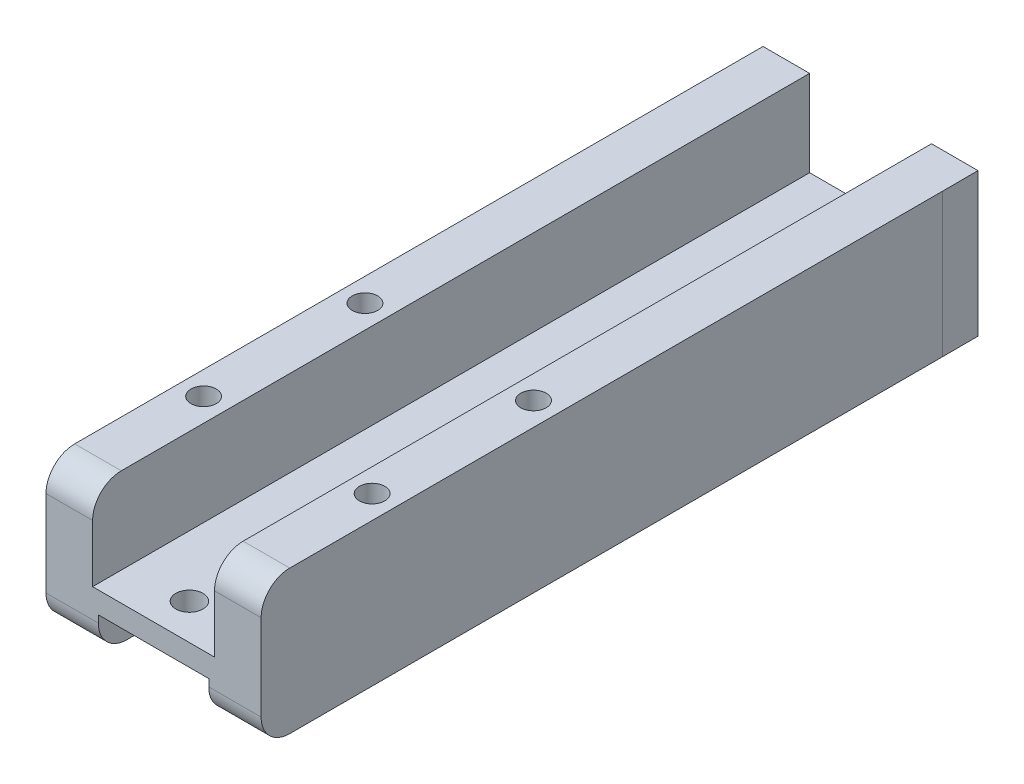
SolidWorks part; units mm, degrees
ref_plane "Front Plane" through (0, 0, 0) normal (0, 0, 1) x (1, 0, 0)
ref_plane "Top Plane" through (0, 0, 0) normal (0, 1, 0) x (1, 0, 0)
ref_plane "Right Plane" through (0, 0, 0) normal (1, 0, 0) x (0, 0, -1)
sketch "Sketch1" plane through (0, 0, 0) normal (0, 1, 0) x (1, 0, 0)
  line L0 (-19.05, 60.325) -> (-19.05, 66.675)
  line L1 (-19.05, -60.325) -> (19.05, -60.325)
  line L2 (-19.05, -60.325) -> (-19.05, 60.325)
  line L4 (19.05, -60.325) -> (19.05, 60.325)
  line L5 (-19.05, -60.325) -> (19.05, 60.325) construction
  line L6 (-19.05, 60.325) -> (19.05, -60.325) construction
  line L8 (19.0295, 66.675) -> (19.05, 60.325)
  line L9 (-19.05, 66.675) -> (19.0295, 66.675)
  line L10 (-22, 66.675) -> (22, 66.675) construction
  point P0 (0, 0)
  dimension "D1" = 38.1
  dimension "D2" = 120.65
  dimension "D3" = 6.35
extrude "Boss-Extrude1" add sketch "Sketch1" along normal blind 38.1
sketch "Sketch2" plane through (0, 38.1, 0) normal (0, 1, 0) x (1, 0, 0)
  line L1 (-10.795, -158.75) -> (10.795, -158.75)
  line L2 (-10.795, -158.75) -> (-10.795, 95.25)
  line L3 (-10.795, 95.25) -> (10.795, 95.25)
  line L4 (10.795, -158.75) -> (10.795, 95.25)
  line L5 (-10.795, -158.75) -> (10.795, 95.25) construction
  line L6 (-10.795, 95.25) -> (10.795, -158.75) construction
  point P0 (0, -31.75)
  dimension "D1" = 254
  dimension "D2" = 21.59
  dimension "D3" = 31.75
extrude "Cut-Extrude1" cut sketch "Sketch2" against normal blind 27.94
sketch "Sketch3" plane through (19.05, 0, 0) normal (1, 0, 0) x (0, 0, -1)
  line L0 (-60.325, 38.1) -> (-60.325, 0) construction
  line L1 (-60.325, 0) -> (60.325, 0) construction
  circle A0 centre (-28.575, 29.21) radius 5.08
  circle A1 centre (34.925, 29.21) radius 5.08
  dimension "D1" = 10.16
  dimension "D2" = 31.75
  dimension "D3" = 29.21
  dimension "D4" = 63.5
sketch "Sketch11" plane through (-19.05, 0, 0) normal (-1, 0, 0) x (0, 0, 1)
  line L0 (60.325, 25.4) -> (35.0008, 25.4)
  line L1 (60.325, 38.1) -> (60.325, 0) construction
  line L3 (-66.675, 0) -> (60.325, 0) construction
  line L7 (-41.6975, 25.4) -> (-60.4984, 25.4)
  line L8 (21.8025, 25.4) -> (-28.4992, 25.4)
  line L10 (-60.4984, 38.1) -> (60.325, 38.1)
  line L11 (60.325, 38.1) -> (60.325, 25.4)
  line L12 (21.8025, 25.4) -> (35.0008, 25.4)
  line L13 (-28.4992, 25.4) -> (-41.6975, 25.4)
  line L14 (-60.4984, 25.4) -> (-66.675, 25.4)
  line L15 (-66.675, 38.1) -> (-66.675, 0) construction
  line L17 (-66.675, 38.1) -> (-60.4984, 38.1)
  line L18 (-66.675, 38.1) -> (-71.3773, 38.1)
  line L19 (-71.3773, 38.1) -> (-71.3773, 25.4)
  line L20 (-71.3773, 25.4) -> (-66.675, 25.4)
  dimension "D2" = 25.4
  dimension "D3" = 12.7
extrude "Cut-Extrude8" cut sketch "Sketch11" against normal through all
sketch "Sketch12" plane through (0, 0, 60.325) normal (0, 0, 1) x (1, 0, 0)
  line L1 (-9.779, -6.35) -> (9.779, -6.35)
  line L2 (-9.779, -6.35) -> (-9.779, 6.35)
  line L3 (-9.779, 6.35) -> (9.779, 6.35)
  line L4 (9.779, -6.35) -> (9.779, 6.35)
  line L5 (-9.779, -6.35) -> (9.779, 6.35) construction
  line L6 (-9.779, 6.35) -> (9.779, -6.35) construction
  point P0 (0, 0)
  dimension "D1" = 19.558
  dimension "D2" = 12.7
extrude "Cut-Extrude9" cut sketch "Sketch12" against normal through all
sketch "Sketch13" plane through (0, 10.16, 0) normal (0, 1, 0) x (1, 0, 0)
  line L0 (10.795, -60.325) -> (-10.795, -60.325) construction
  line L2 (0, 47.625) -> (0, -53.975) construction
  circle A0 centre (0, -53.975) radius 2.413
  circle A1 centre (0, 47.625) radius 2.413
  circle A2 centre (0, -3.175) radius 2.413
  dimension "D1" = 4.826
  dimension "D2" = 6.35
  dimension "D3" = 101.6
extrude "Cut-Extrude10" cut sketch "Sketch13" against normal through all
sketch "Sketch14" plane through (0, 25.4, 0) normal (0, 1, 0) x (1, 0, 0)
  point P0 (-14.9225, -36.5306)
  point P1 (-14.9225, -7.9556)
  point P3 (14.9225, -7.9556)
  point P5 (14.9225, -36.5306)
hole_wizard "#8 Clearance Hole1" positions "Sketch14" profile "Sketch16" hole size "#8" standard "ANSI Inch" end condition through all
sketch "Sketch16" plane through (-14.9225, 25.4, 36.5306) normal (1, 0, 0) x (0, 0, 1)
  line L0 (0, 0) -> (0, 25.4)
  line L1 (0, 25.4) -> (2.2479, 25.4)
  line L2 (2.2479, 25.4) -> (2.2479, 0)
  line L5 (2.2479, 0) -> (0, 0)
  line L11 (0, -6.35) -> (0, 107.95) construction
  dimension "Thru Hole Dia." = 4.4958
  dimension "Thru Hole Depth" = 25.4
fillet "Fillet2" radius 5.08 4 edges at (14.9225, 25.4, 60.325) (-14.9225, 25.4, 60.325) (14.4145, 0, 60.325) (-14.4145, 0, 60.325)
